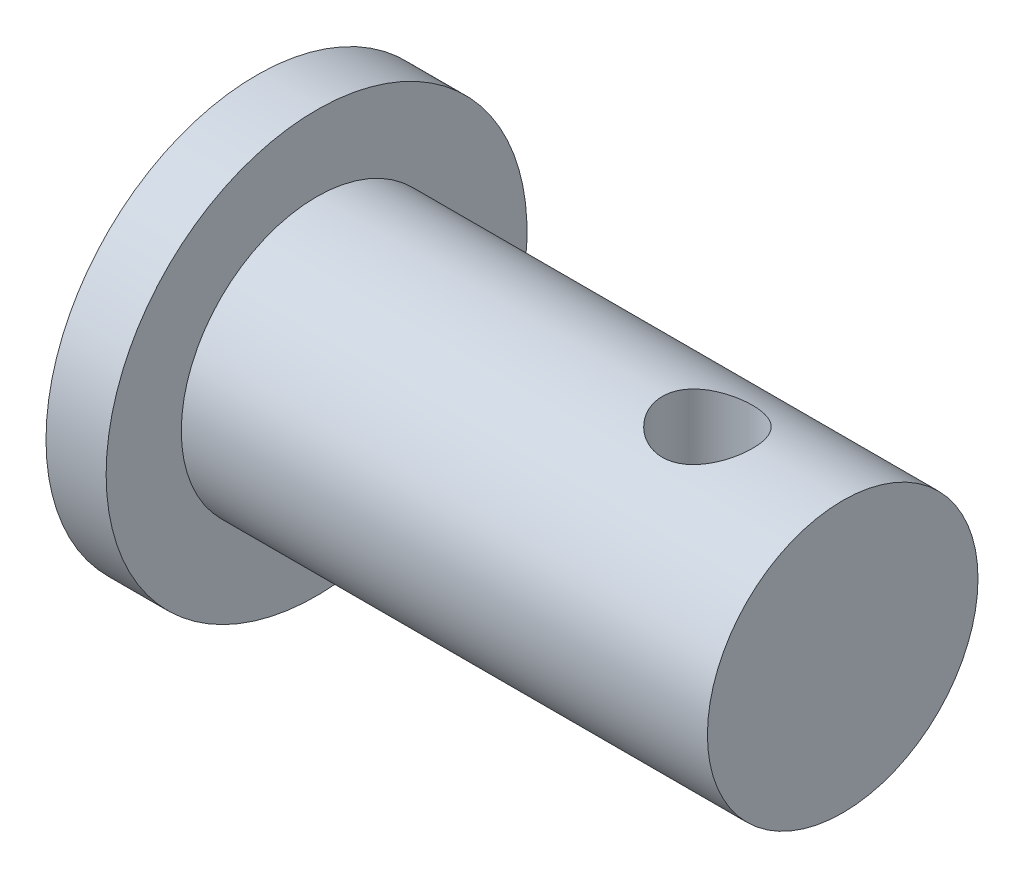
SolidWorks part; units mm, degrees
material "Brass"
ref_plane "Front Plane" through (0, 0, 0) normal (0, 0, 1) x (1, 0, 0)
ref_plane "Top Plane" through (0, 0, 0) normal (0, 1, 0) x (1, 0, 0)
ref_plane "Right Plane" through (0, 0, 0) normal (1, 0, 0) x (0, 0, -1)
sketch "Sketch1" plane through (0, 0, 0) normal (1, 0, 0) x (0, 0, -1)
  circle A0 centre (0, 0) radius 4.5
  dimension "D1" = 9
extrude "Boss-Extrude1" add sketch "Sketch1" along normal blind 19.5
sketch "Sketch2" plane through (0, 0, 0) normal (-1, 0, 0) x (0, 0, 1)
  circle A0 centre (0, 0) radius 7
  dimension "D1" = 14
extrude "Boss-Extrude2" add sketch "Sketch2" against normal blind 2
sketch "Sketch3" plane through (0, 0, 0) normal (0, 1, 0) x (1, 0, 0)
  line L0 (19.5, -4.5) -> (19.5, 4.5) construction
  circle A0 centre (15, 0) radius 1.5
  dimension "D1" = 3
  dimension "D2" = 4.5
extrude "Cut-Extrude1" cut sketch "Sketch3" against normal through all both and the other way through all
